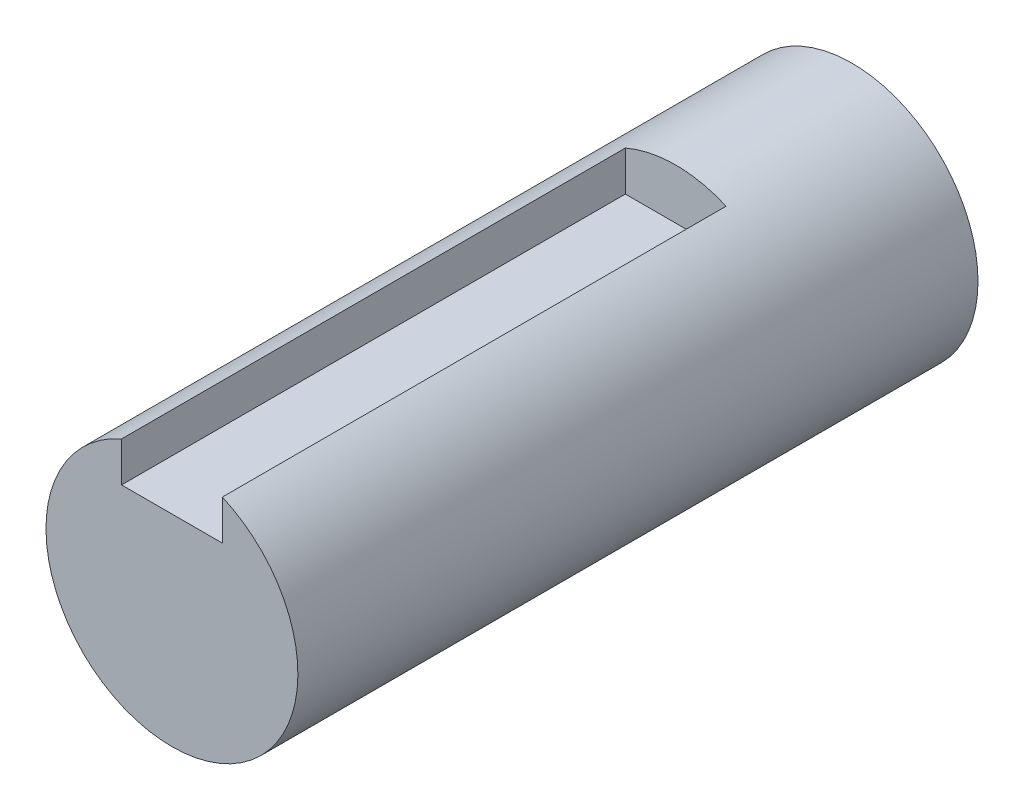
SolidWorks part; units mm, degrees
ref_plane "Front Plane" through (0, 0, 0) normal (0, 0, 1) x (1, 0, 0)
ref_plane "Top Plane" through (0, 0, 0) normal (0, 1, 0) x (1, 0, 0)
ref_plane "Right Plane" through (0, 0, 0) normal (1, 0, 0) x (0, 0, -1)
sketch "Sketch1" plane through (0, 0, 0) normal (0, 0, 1) x (1, 0, 0)
  circle A0 centre (0, 0) radius 5
  dimension "D1" = 10
extrude "Boss-Extrude1" add sketch "Sketch1" along normal blind 27
sketch "Sketch2" plane through (0, 0, 27) normal (0, 0, 1) x (1, 0, 0)
  line L1 (-2, 7) -> (2, 7)
  line L2 (-2, 7) -> (-2, 3)
  line L3 (-2, 3) -> (2, 3)
  line L4 (2, 7) -> (2, 3)
  line L5 (-2, 7) -> (2, 3) construction
  line L6 (-2, 3) -> (2, 7) construction
  circle A0 centre (0, 0) radius 5 construction
  point P0 (0, 5)
  point P5 (0, 5)
  dimension "D1" = 4
extrude "Cut-Extrude1" cut sketch "Sketch2" against normal blind 20 contours L2 L1 L4 L3
